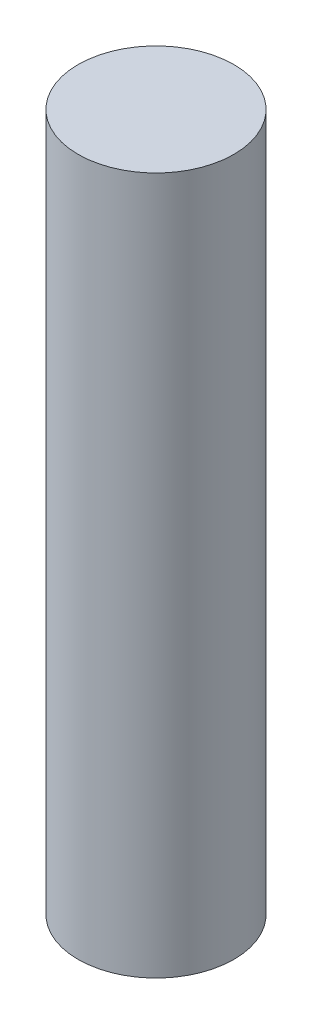
SolidWorks part; units mm, degrees
ref_plane "Front Plane" through (0, 0, 0) normal (0, 0, 1) x (1, 0, 0)
ref_plane "Top Plane" through (0, 0, 0) normal (0, 1, 0) x (1, 0, 0)
ref_plane "Right Plane" through (0, 0, 0) normal (1, 0, 0) x (0, 0, -1)
sketch "Sketch1" plane through (0, 0, 0) normal (0, 1, 0) x (1, 0, 0)
  circle A0 centre (0, 0) radius 3.35
  dimension "D1" = 6.7
extrude "Boss-Extrude1" add sketch "Sketch1" along normal blind 30
